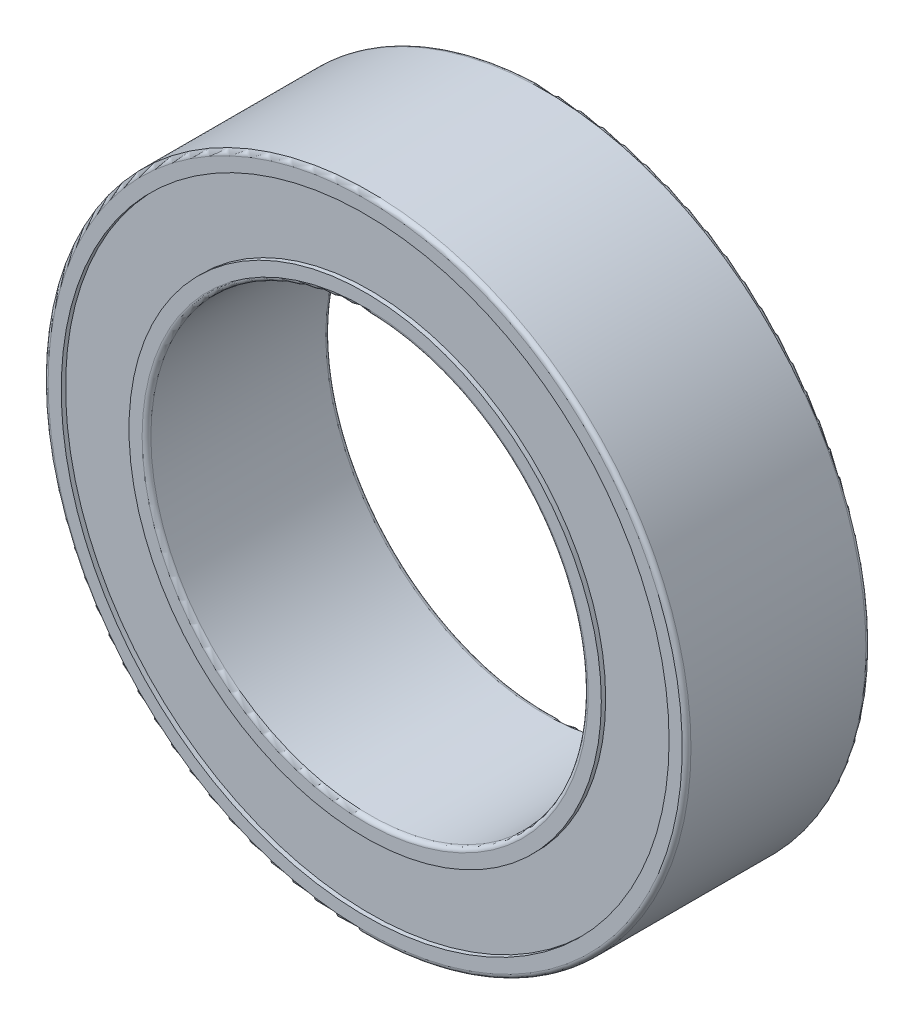
SolidWorks part; units mm, degrees
material "Plain Carbon Steel"
ref_plane "Front Plane" through (0, 0, 0) normal (0, 0, 1) x (1, 0, 0)
ref_plane "Top Plane" through (0, 0, 0) normal (0, 1, 0) x (1, 0, 0)
ref_plane "Right Plane" through (0, 0, 0) normal (1, 0, 0) x (0, 0, -1)
sketch "Sketch1" plane through (0, 0, 0) normal (1, 0, 0) x (0, 0, -1)
  line L0 (-14.88, 0) -> (16.8, 0) construction
  line L1 (-2.1, 5) -> (-2.1, 5.4)
  line L2 (-2.1, 5.4) -> (-2, 5.4)
  line L3 (2.1, 5) -> (2.1, 5.4)
  line L4 (2.1, 5.4) -> (2, 5.4)
  line L5 (-2, 5.4) -> (-2, 6.95)
  line L6 (-2, 6.95) -> (-2.1, 6.95)
  line L7 (2, 5.4) -> (2, 6.95)
  line L8 (2, 6.95) -> (2.1, 6.95)
  line L9 (-2.1, 6.95) -> (-2.1, 7.35)
  line L10 (-2.1, 7.35) -> (2.1, 7.35)
  line L11 (0, 7.35) -> (0, 0) construction
  line L12 (-2.1, 5) -> (2.1, 5)
  line L13 (-2, 6.175) -> (0, 6.175) construction
  line L14 (2.1, 6.95) -> (2.1, 7.35)
  point P11 (0, 5)
  dimension "D1" = 10
  dimension "D2" = 14.7
  dimension "D3" = 0.4
  dimension "D4" = 0.1
  dimension "D5" = 4.2
revolve "Revolve1" add sketch "Sketch1" angle 360 about L0
fillet "Fillet1" radius 0.1 4 edges at (5, 0, 2.1) (5, 0, -2.1) (7.35, 0, -2.1) (7.35, 0, 2.1)
